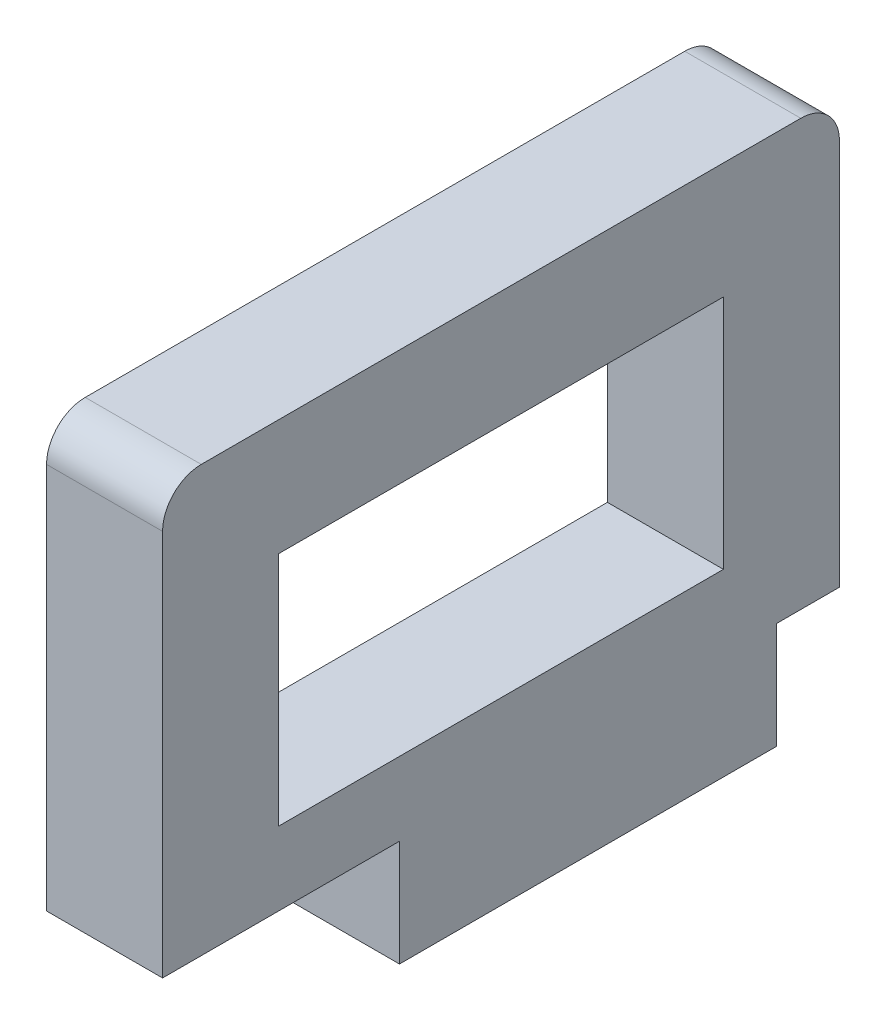
SolidWorks part; units mm, degrees
ref_plane "Front Plane" through (0, 0, 0) normal (0, 0, 1) x (1, 0, 0)
ref_plane "Top Plane" through (0, 0, 0) normal (0, 1, 0) x (1, 0, 0)
ref_plane "Right Plane" through (0, 0, 0) normal (1, 0, 0) x (0, 0, -1)
sketch "Sketch1" plane through (0, 0, 0) normal (1, 0, 0) x (0, 0, -1)
  line L0 (17.5, -9.9) -> (17.5, 12.1)
  line L1 (-11.5, -6.1) -> (11.5, -6.1)
  line L2 (-11.5, -6.1) -> (-11.5, 6.1)
  line L3 (-11.5, 6.1) -> (11.5, 6.1)
  line L4 (11.5, -6.1) -> (11.5, 6.1)
  line L5 (-11.5, -6.1) -> (11.5, 6.1) construction
  line L6 (-11.5, 6.1) -> (11.5, -6.1) construction
  line L7 (17.5, 12.1) -> (-17.5, 12.1)
  line L8 (-17.5, 12.1) -> (-17.5, -9.9)
  line L14 (0, 59.1719) -> (0, -65.0812) construction
  line L16 (-17.5, -9.9) -> (-5.25, -9.9)
  line L17 (-5.25, -9.9) -> (-5.25, -15.4)
  line L18 (-5.25, -15.4) -> (14.25, -15.4)
  line L19 (14.25, -15.4) -> (14.25, -9.9)
  line L20 (14.25, -9.9) -> (17.5, -9.9)
  point P0 (0, 0)
  point P16 (0, 12.1)
  dimension "D1" = 23
  dimension "D2" = 6
  dimension "D3" = 5.5
  dimension "D4" = 35
  dimension "D5" = 19.5
  dimension "D6" = 3.25
  dimension "D7" = 22
extrude "Boss-Extrude1" add sketch "Sketch1" along normal blind 6
fillet "Fillet1" radius 2 2 edges at (3, 12.1, 17.5) (3, 12.1, -17.5)
